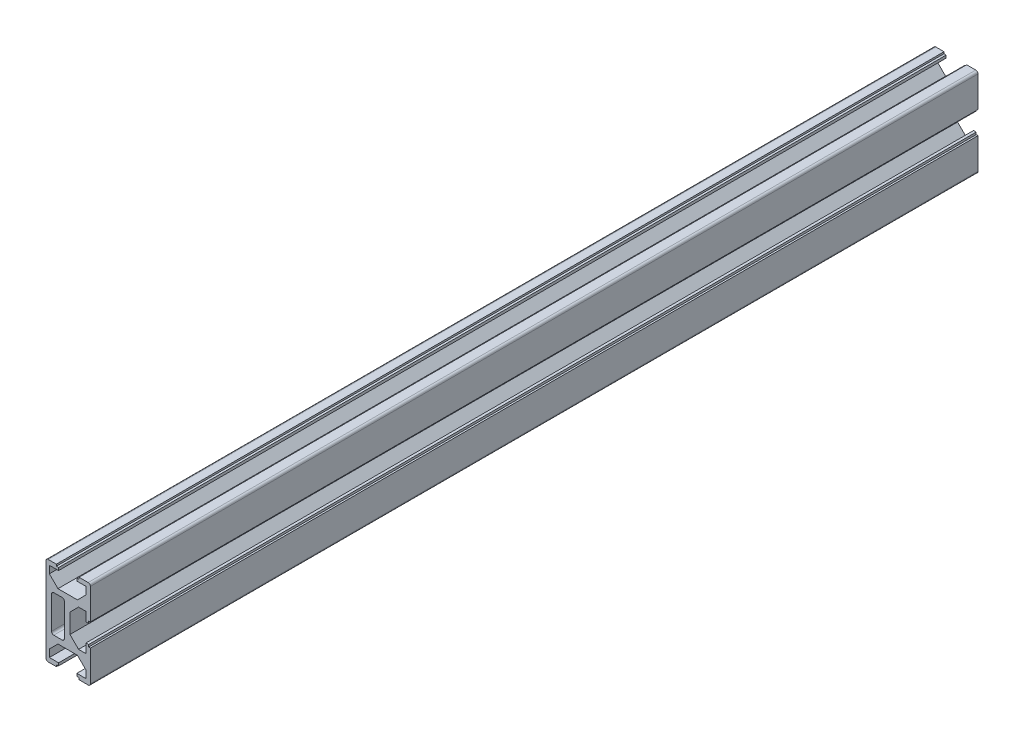
SolidWorks part; units mm, degrees
ref_plane "前视基准面" through (0, 0, 0) normal (0, 0, 1) x (1, 0, 0)
ref_plane "上视基准面" through (0, 0, 0) normal (0, 1, 0) x (1, 0, 0)
ref_plane "右视基准面" through (0, 0, 0) normal (1, 0, 0) x (0, 0, -1)
sketch "草图30" plane through (0, 0, 0) normal (0, 0, 1) x (1, 0, 0)
  line L0 (-10, 8.9627) -> (10, 8.9627) construction
  point P2 (0, 8.9627)
  line B0 (-1.7, 7.3) -> (-1.7, -7.3)
  line B1 (-2.7, -8.3) -> (-6.5, -8.3)
  line B2 (-7.5, -7.3) -> (-7.5, 7.3)
  line B3 (-6.5, 8.3) -> (-2.7, 8.3)
  line B4 (0.8, 4.3858) -> (4.6642, 8.25)
  line B5 (4.6642, 8.25) -> (8, 8.25)
  line B6 (8, 8.25) -> (8, 4.1)
  line B7 (8, 4.1) -> (9.2, 4.1)
  line B8 (9.2, 4.1) -> (9.2, 5.1)
  line B9 (9.2, 5.1) -> (10, 5.1)
  line B10 (10, 5.1) -> (10, 19)
  line B11 (9, 20) -> (4.8784, 20)
  line B12 (4.8784, 20) -> (4.8784, 19.2)
  line B13 (4.8784, 19.2) -> (3.8784, 19.2)
  line B14 (3.8784, 19.2) -> (3.8784, 18)
  line B15 (3.8784, 18) -> (8.0284, 18)
  line B16 (8.0284, 18) -> (8.0284, 14.6642)
  line B17 (8.0284, 14.6642) -> (4.1642, 10.8)
  line B18 (4.1642, 10.8) -> (-4.6074, 10.8)
  line B19 (-4.6074, 10.8) -> (-8.4716, 14.6642)
  line B20 (-8.4716, 14.6642) -> (-8.4716, 18)
  line B21 (-8.4716, 18) -> (-4.3216, 18)
  line B22 (-4.3216, 18) -> (-4.3216, 19.2)
  line B23 (-4.3216, 19.2) -> (-5.3216, 19.2)
  line B24 (-5.3216, 19.2) -> (-5.3216, 20)
  line B25 (-5.3216, 20) -> (-9, 20)
  line B26 (-10, 19) -> (-10, -19)
  line B27 (-9, -20) -> (-5.3216, -20)
  line B28 (-5.3216, -20) -> (-5.3216, -19.2)
  line B29 (-5.3216, -19.2) -> (-4.3216, -19.2)
  line B30 (-4.3216, -19.2) -> (-4.3216, -18)
  line B31 (-4.3216, -18) -> (-8.4716, -18)
  line B32 (-8.4716, -18) -> (-8.4716, -14.6642)
  line B33 (-8.4716, -14.6642) -> (-4.6074, -10.8)
  line B34 (-4.6074, -10.8) -> (4.1642, -10.8)
  line B35 (4.1642, -10.8) -> (8.0284, -14.6642)
  line B36 (8.0284, -14.6642) -> (8.0284, -18)
  line B37 (8.0284, -18) -> (3.8784, -18)
  line B38 (3.8784, -18) -> (3.8784, -19.2)
  line B39 (3.8784, -19.2) -> (4.8784, -19.2)
  line B40 (4.8784, -19.2) -> (4.8784, -20)
  line B41 (4.8784, -20) -> (9, -20)
  line B42 (10, -19) -> (10, -5.1)
  line B43 (10, -5.1) -> (9.2, -5.1)
  line B44 (9.2, -5.1) -> (9.2, -4.1)
  line B45 (9.2, -4.1) -> (8, -4.1)
  line B46 (8, -4.1) -> (8, -8.25)
  line B47 (8, -8.25) -> (4.6642, -8.25)
  line B48 (4.6642, -8.25) -> (0.8, -4.3858)
  line B49 (0.8, -4.3858) -> (0.8, 4.3858)
  arc B50 (-1.7, 7.3) -> (-2.7, 8.3) centre (-2.7, 7.3) ccw
  arc B51 (-2.7, -8.3) -> (-1.7, -7.3) centre (-2.7, -7.3) ccw
  arc B52 (-7.5, -7.3) -> (-6.5, -8.3) centre (-6.5, -7.3) ccw
  arc B53 (-6.5, 8.3) -> (-7.5, 7.3) centre (-6.5, 7.3) ccw
  arc B54 (10, 19) -> (9, 20) centre (9, 19) ccw
  arc B55 (-9, 20) -> (-10, 19) centre (-9, 19) ccw
  arc B56 (-10, -19) -> (-9, -20) centre (-9, -19) ccw
  arc B57 (9, -20) -> (10, -19) centre (9, -19) ccw
sketch_block_instance "块2-1"
sketch_block "块2"
extrude "凸台-拉伸3" add sketch "草图30" along normal blind 400
ref_plane "基准面1" through (0, 0, 50) normal (0, 0, 1) x (1, 0, 0)
ref_plane "基准面2" through (0, 20, 0) normal (0, 1, 0) x (1, 0, 0)
ref_plane "基准面3" through (0, -20, 0) normal (0, 1, 0) x (1, 0, 0)
ref_plane "基准面4" through (10, 0, 0) normal (1, 0, 0) x (0, 0, -1)
ref_plane "基准面5" through (-10, 0, 0) normal (1, 0, 0) x (0, 0, -1)
sketch "草图19" plane through (0, 0, 0) normal (0, 0, 1) x (1, 0, 0)
  line L0 (0, 0) -> (0, 11.6901) construction
  line L1 (0, 0) -> (10.3437, 0) construction
sketch "草图20" plane through (0, 0, 0) normal (0, 1, 0) x (1, 0, 0)
  line L0 (0, 0) -> (0, 3.5576) construction
ref_point "点1"
sketch "草图2" [suppressed] plane through (0, 0, 0) normal (1, 0, 0) x (0, 0, -1)
  line L0 (-370, -20) -> (-330, 20)
  line L1 (11.189, -20) -> (-11.189, -20) construction
  line L2 (11.189, 20) -> (-11.189, 20) construction
  line L3 (-330, 20) -> (-370, 20)
  line L4 (-370, 11.189) -> (-370, -11.189) construction
  line L5 (-370, 20) -> (-370, -20)
  dimension "D1" = 45
extrude "切除-拉伸1" [suppressed] cut sketch "草图2" against normal through all and the other way through all
sketch "草图3" [suppressed] plane through (0, 0, 0) normal (1, 0, 0) x (0, 0, -1)
  line L0 (0, -20) -> (-40, 20)
  line L1 (11.189, -20) -> (-11.189, -20) construction
  line L2 (11.189, 20) -> (-11.189, 20) construction
  line L3 (-40, 20) -> (0, 20)
  line L4 (0, 20) -> (0, -20)
  line L5 (0, 11.189) -> (0, -11.189) construction
  dimension "D1" = 45
extrude "切除-拉伸2" [suppressed] cut sketch "草图3" against normal through all and the other way through all
sketch "草图4" [suppressed] plane through (0, 0, 0) normal (1, 0, 0) x (0, 0, -1)
  line L0 (-370, 20) -> (-330, -20)
  line L1 (11.189, 20) -> (-11.189, 20) construction
  line L2 (-370, 11.189) -> (-370, -11.189) construction
  line L3 (11.189, -20) -> (-11.189, -20) construction
  line L4 (-330, -20) -> (-370, -20)
  line L5 (-370, -20) -> (-370, 20)
  dimension "D1" = 45
extrude "切除-拉伸3" [suppressed] cut sketch "草图4" against normal through all and the other way through all
sketch "草图5" [suppressed] plane through (0, 0, 0) normal (1, 0, 0) x (0, 0, -1)
  line L0 (0, 20) -> (-40, -20)
  line L1 (11.189, 20) -> (-11.189, 20) construction
  line L2 (11.189, -20) -> (-11.189, -20) construction
  line L3 (-40, -20) -> (0, -20)
  line L4 (0, -20) -> (0, 20)
  line L5 (0, 11.189) -> (0, -11.189) construction
  dimension "D1" = 45
extrude "切除-拉伸4" [suppressed] cut sketch "草图5" against normal through all and the other way through all
sketch "草图6" [suppressed] plane through (0, 0, 0) normal (0, 1, 0) x (1, 0, 0)
  line L0 (-10, -370) -> (10, -350)
  line L1 (-10, -22) -> (-10, 22) construction
  line L2 (-11.189, -370) -> (11.189, -370) construction
  line L3 (10, -22) -> (10, 22) construction
  line L4 (10, -350) -> (10, -370)
  line L5 (10, -370) -> (-10, -370)
  dimension "D1" = 45
extrude "切除-拉伸5" [suppressed] cut sketch "草图6" against normal through all and the other way through all
sketch "草图7" [suppressed] plane through (0, 0, 0) normal (0, 1, 0) x (1, 0, 0)
  line L0 (-10, 0) -> (10, -20)
  line L1 (-10, -22) -> (-10, 22) construction
  line L2 (10, -22) -> (10, 22) construction
  line L3 (10, -20) -> (10, 0)
  line L4 (-11.189, 0) -> (11.189, 0) construction
  line L5 (10, 0) -> (-10, 0)
  dimension "D1" = 45
extrude "切除-拉伸6" [suppressed] cut sketch "草图7" against normal through all and the other way through all
sketch "草图8" [suppressed] plane through (0, 0, 0) normal (0, 1, 0) x (1, 0, 0)
  line L0 (-10, -350) -> (10, -370)
  line L1 (-10, -22) -> (-10, 22) construction
  line L2 (10, -22) -> (10, 22) construction
  line L3 (-11.189, -370) -> (11.189, -370) construction
  line L4 (10, -370) -> (-10, -370)
  line L5 (-10, -370) -> (-10, -350)
  dimension "D1" = 45
extrude "切除-拉伸7" [suppressed] cut sketch "草图8" against normal through all and the other way through all
sketch "草图9" [suppressed] plane through (0, 0, 0) normal (0, 1, 0) x (1, 0, 0)
  line L0 (10, 0) -> (-10, -20)
  line L1 (10, -22) -> (10, 22) construction
  line L2 (-11.189, 0) -> (11.189, 0) construction
  line L3 (-10, -22) -> (-10, 22) construction
  line L4 (-10, -20) -> (-10, 0)
  line L5 (-10, 0) -> (10, 0)
  dimension "D1" = 45
extrude "切除-拉伸8" [suppressed] cut sketch "草图9" against normal through all and the other way through all
sketch "草图18" [suppressed] plane through (0, 0, 0) normal (0, 1, 0) x (1, 0, 0)
  line L0 (-10, -307) -> (10, -307)
  line L1 (-10, -22) -> (-10, 22) construction
  line L2 (10, -22) -> (10, 22) construction
  line L3 (10, -307) -> (10, -300)
  line L4 (10, -300) -> (1.5, -300)
  line L5 (1.5, -300) -> (1.5, -302.5)
  line L6 (1.5, -302.5) -> (-10, -302.5)
  line L7 (-10, -302.5) -> (-10, -307)
  line L8 (-11.189, -370) -> (11.189, -370) construction
  dimension "D1" = 63
  dimension "D2" = 7
  dimension "D3" = 4.5
  dimension "D4" = 8.5
revolve "切除-旋转5" [suppressed] cut sketch "草图18" angle 360 about L0
other "表格阵列1" [suppressed] parameters "D0"=26, "D1"=0, "D2"=52, "D3"=0, "D4"=78, "D5"=0, "D6"=104, "D7"=0
sketch "草图21" [suppressed] plane through (0, 0, 0) normal (0, 1, 0) x (1, 0, 0)
  line L0 (-10, -63) -> (10, -63)
  line L1 (-10, -22) -> (-10, 22) construction
  line L2 (10, -22) -> (10, 22) construction
  line L3 (10, -63) -> (10, -70)
  line L4 (10, -70) -> (1.5, -70)
  line L5 (1.5, -70) -> (1.5, -67.5)
  line L6 (1.5, -67.5) -> (-10, -67.5)
  line L7 (-10, -67.5) -> (-10, -63)
  dimension "D1" = 7
  dimension "D2" = 4.5
  dimension "D3" = 8.5
  dimension "D4" = 63
revolve "切除-旋转6" [suppressed] cut sketch "草图21" angle 360 about L0
other "表格阵列2" [suppressed] parameters "D0"=26, "D1"=0, "D2"=52, "D3"=0, "D4"=78, "D5"=0, "D6"=104, "D7"=0
sketch "草图22" [suppressed] plane through (0, 0, 0) normal (1, 0, 0) x (0, 0, -1)
  line L0 (-307, 20) -> (-307, -20)
  line L1 (11.189, 20) -> (-11.189, 20) construction
  line L2 (11.189, -20) -> (-11.189, -20) construction
  line L3 (-307, -20) -> (-302.5, -20)
  line L4 (-302.5, -20) -> (-302.5, 11.5)
  line L5 (-302.5, 11.5) -> (-300, 11.5)
  line L6 (-300, 11.5) -> (-300, 20)
  line L7 (-300, 20) -> (-307, 20)
  line L8 (-370, 11.189) -> (-370, -11.189) construction
  dimension "D1" = 7
  dimension "D2" = 4.5
  dimension "D3" = 8.5
  dimension "D4" = 63
revolve "切除-旋转7" [suppressed] cut sketch "草图22" angle 360 about L0
other "表格阵列3" [suppressed] parameters "D0"=26, "D1"=0, "D2"=52, "D3"=0, "D4"=78, "D5"=0, "D6"=104, "D7"=0
sketch "草图23" [suppressed] plane through (0, 0, 0) normal (1, 0, 0) x (0, 0, -1)
  line L0 (-63, 20) -> (-70, 20)
  line L1 (11.189, 20) -> (-11.189, 20) construction
  line L2 (-70, 20) -> (-70, 11.5)
  line L3 (-70, 11.5) -> (-67.5, 11.5)
  line L4 (-67.5, 11.5) -> (-67.5, -20)
  line L5 (11.189, -20) -> (-11.189, -20) construction
  line L6 (-67.5, -20) -> (-63, -20)
  line L7 (-63, -20) -> (-63, 20)
  dimension "D1" = 7
  dimension "D2" = 4.5
  dimension "D3" = 8.5
  dimension "D4" = 63
revolve "切除-旋转8" [suppressed] cut sketch "草图23" angle 360 about L7
other "表格阵列4" [suppressed] parameters "D0"=26, "D1"=0, "D2"=52, "D3"=0, "D4"=78, "D5"=0, "D6"=104, "D7"=0
sketch "草图24" [suppressed] plane through (10, 0, 0) normal (1, 0, 0) x (0, 0, -1)
  line L0 (-370, 11.189) -> (-370, -11.189) construction
  circle A0 centre (-320, 0) radius 4.25
  dimension "D1" = 8.5
  dimension "D2" = 50
extrude "切除-拉伸13" [suppressed] cut sketch "草图24" against normal through all
other "表格阵列5" [suppressed] parameters "D0"=26, "D1"=0, "D2"=52, "D3"=0, "D4"=78, "D5"=0, "D6"=104, "D7"=0
sketch "草图25" [suppressed] plane through (10, 0, 0) normal (1, 0, 0) x (0, 0, -1)
  circle A0 centre (-50, 0) radius 4.25
  dimension "D1" = 8.5
  dimension "D2" = 50
extrude "切除-拉伸14" [suppressed] cut sketch "草图25" against normal through all
other "表格阵列6" [suppressed] parameters "D0"=26, "D1"=0, "D2"=52, "D3"=0, "D4"=78, "D5"=0, "D6"=104, "D7"=0
sketch "草图26" [suppressed] plane through (0, 20, 0) normal (0, 1, 0) x (1, 0, 0)
  line L0 (-11.189, -370) -> (11.189, -370) construction
  circle A0 centre (0, -320) radius 4.25
  dimension "D1" = 8.5
  dimension "D2" = 50
extrude "切除-拉伸15" [suppressed] cut sketch "草图26" against normal through all
other "表格阵列7" [suppressed] parameters "D0"=26, "D1"=0, "D2"=52, "D3"=0, "D4"=78, "D5"=0, "D6"=104, "D7"=0
sketch "草图27" [suppressed] plane through (0, 20, 0) normal (0, 1, 0) x (1, 0, 0)
  circle A0 centre (0, -50) radius 4.25
  dimension "D1" = 8.5
  dimension "D2" = 50
extrude "切除-拉伸16" [suppressed] cut sketch "草图27" against normal through all
other "表格阵列8" [suppressed] parameters "D0"=26, "D1"=0, "D2"=52, "D3"=0, "D4"=78, "D5"=0, "D6"=104, "D7"=0
sketch "草图31" [suppressed] plane through (0, 0, 0) normal (0, 1, 0) x (1, 0, 0)
  line L0 (-10, -307) -> (-10, -300)
  line L1 (-10, -300) -> (-1.5, -300)
  line L2 (-1.5, -300) -> (-1.5, -302.5)
  line L3 (-1.5, -302.5) -> (10, -302.5)
  line L4 (10, -302.5) -> (10, -307)
  line L5 (10, -307) -> (-10, -307)
  line L6 (-10, -22) -> (-10, 22) construction
  line L7 (10, -22) -> (10, 22) construction
  line L8 (-11.189, -370) -> (11.189, -370) construction
  dimension "D1" = 4.5
  dimension "D2" = 7
  dimension "D3" = 8.5
  dimension "D4" = 63
revolve "切除-旋转9" [suppressed] cut sketch "草图31" angle 360 about L5
other "表格阵列9" [suppressed] parameters "D0"=26, "D1"=0, "D2"=52, "D3"=0, "D4"=78, "D5"=0, "D6"=104, "D7"=0
sketch "草图32" [suppressed] plane through (0, 0, 0) normal (0, 1, 0) x (1, 0, 0)
  line L0 (10, -63) -> (10, -67.5)
  line L1 (10, -67.5) -> (-1.5, -67.5)
  line L2 (-1.5, -67.5) -> (-1.5, -70)
  line L3 (-1.5, -70) -> (-10, -70)
  line L4 (-10, -70) -> (-10, -63)
  line L5 (-10, -63) -> (10, -63)
  line L6 (-10, -22) -> (-10, 22) construction
  line L7 (10, -22) -> (10, 22) construction
  dimension "D1" = 7
  dimension "D2" = 8.5
  dimension "D3" = 4.5
  dimension "D4" = 63
revolve "切除-旋转10" [suppressed] cut sketch "草图32" angle 360 about L5
other "表格阵列10" [suppressed] parameters "D0"=26, "D1"=0, "D2"=52, "D3"=0, "D4"=78, "D5"=0, "D6"=104, "D7"=0
sketch "草图33" [suppressed] plane through (0, 0, 0) normal (1, 0, 0) x (0, 0, -1)
  line L0 (-307, 20) -> (-302.5, 20)
  line L1 (-302.5, 20) -> (-302.5, -11.5)
  line L2 (-302.5, -11.5) -> (-300, -11.5)
  line L3 (-300, -11.5) -> (-300, -20)
  line L4 (-300, -20) -> (-307, -20)
  line L5 (-307, -20) -> (-307, 20)
  line L6 (11.189, -20) -> (-11.189, -20) construction
  line L7 (11.189, 20) -> (-11.189, 20) construction
  line L8 (-370, 11.189) -> (-370, -11.189) construction
  dimension "D1" = 4.5
  dimension "D2" = 7
  dimension "D3" = 8.5
  dimension "D4" = 63
revolve "切除-旋转11" [suppressed] cut sketch "草图33" angle 360 about L5
other "表格阵列11" [suppressed] parameters "D0"=26, "D1"=0, "D2"=52, "D3"=0, "D4"=78, "D5"=0, "D6"=104, "D7"=0
sketch "草图34" [suppressed] plane through (0, 0, 0) normal (1, 0, 0) x (0, 0, -1)
  line L0 (-63, 20) -> (-67.5, 20)
  line L1 (-67.5, 20) -> (-67.5, -11.5)
  line L2 (-67.5, -11.5) -> (-70, -11.5)
  line L3 (-70, -11.5) -> (-70, -20)
  line L4 (-70, -20) -> (-63, -20)
  line L5 (-63, -20) -> (-63, 20)
  line L6 (11.189, -20) -> (-11.189, -20) construction
  line L7 (11.189, 20) -> (-11.189, 20) construction
  dimension "D1" = 4.5
  dimension "D2" = 7
  dimension "D3" = 8.5
  dimension "D4" = 63
revolve "切除-旋转12" [suppressed] cut sketch "草图34" angle 360 about L5
other "表格阵列13" [suppressed] parameters "D0"=26, "D1"=0, "D2"=52, "D3"=0, "D4"=78, "D5"=0, "D6"=104, "D7"=0
equation "\"L\"= 400"
equation "\"D1@凸台-拉伸3\"=\"L\""
